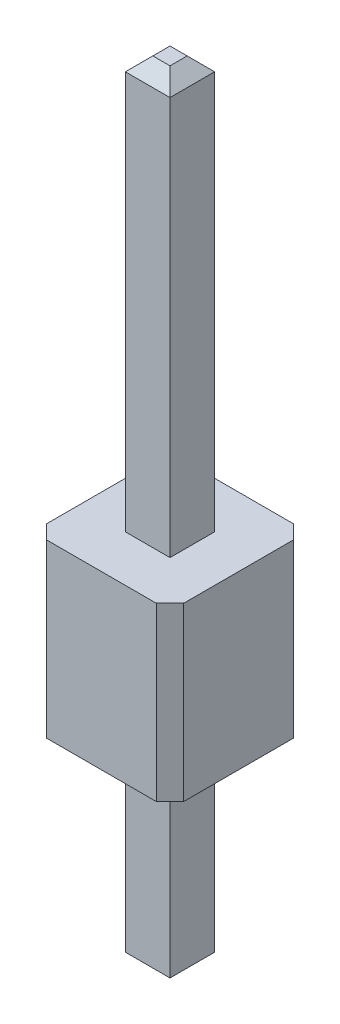
SolidWorks part; units mm, degrees
ref_plane "Front Plane" through (0, 0, 0) normal (0, 0, 1) x (1, 0, 0)
ref_plane "Top Plane" through (0, 0, 0) normal (0, 1, 0) x (1, 0, 0)
ref_plane "Right Plane" through (0, 0, 0) normal (1, 0, 0) x (0, 0, -1)
sketch "Sketch1" plane through (0, 0, 0) normal (0, 1, 0) x (1, 0, 0)
  line L1 (-1, -1) -> (1, -1)
  line L2 (-1, -1) -> (-1, 1)
  line L3 (-1, 1) -> (1, 1)
  line L4 (1, -1) -> (1, 1)
  line L5 (-1, -1) -> (1, 1) construction
  line L6 (-1, 1) -> (1, -1) construction
  point P0 (0, 0)
  dimension "D1" = 2
  dimension "D2" = 2
extrude "Boss-Extrude1" add sketch "Sketch1" along normal blind 2.5
sketch "Sketch2" plane through (0, 2.5, 0) normal (0, 1, 0) x (1, 0, 0)
  line L1 (-0.325, -0.325) -> (0.325, -0.325)
  line L2 (-0.325, -0.325) -> (-0.325, 0.325)
  line L3 (-0.325, 0.325) -> (0.325, 0.325)
  line L4 (0.325, -0.325) -> (0.325, 0.325)
  line L5 (-0.325, -0.325) -> (0.325, 0.325) construction
  line L6 (-0.325, 0.325) -> (0.325, -0.325) construction
  point P0 (0, 0)
  dimension "D1" = 0.65
  dimension "D2" = 0.65
extrude "Boss-Extrude2" add sketch "Sketch2" along normal blind 6 and the other way blind 5.5
chamfer "Chamfer1" distance 0.2 angle 45 4 edges at (-1, 1.25, -1) (1, 1.25, -1) (-1, 1.25, 1) (1, 1.25, 1)
chamfer "Chamfer2" distance 0.2 angle 45 8 edges at (0, 8.5, 0.325) (-0.325, 8.5, 0) (0, 8.5, -0.325) (0.325, 8.5, 0) (0, -3, 0.325) (-0.325, -3, 0) (0, -3, -0.325) (0.325, -3, 0)
